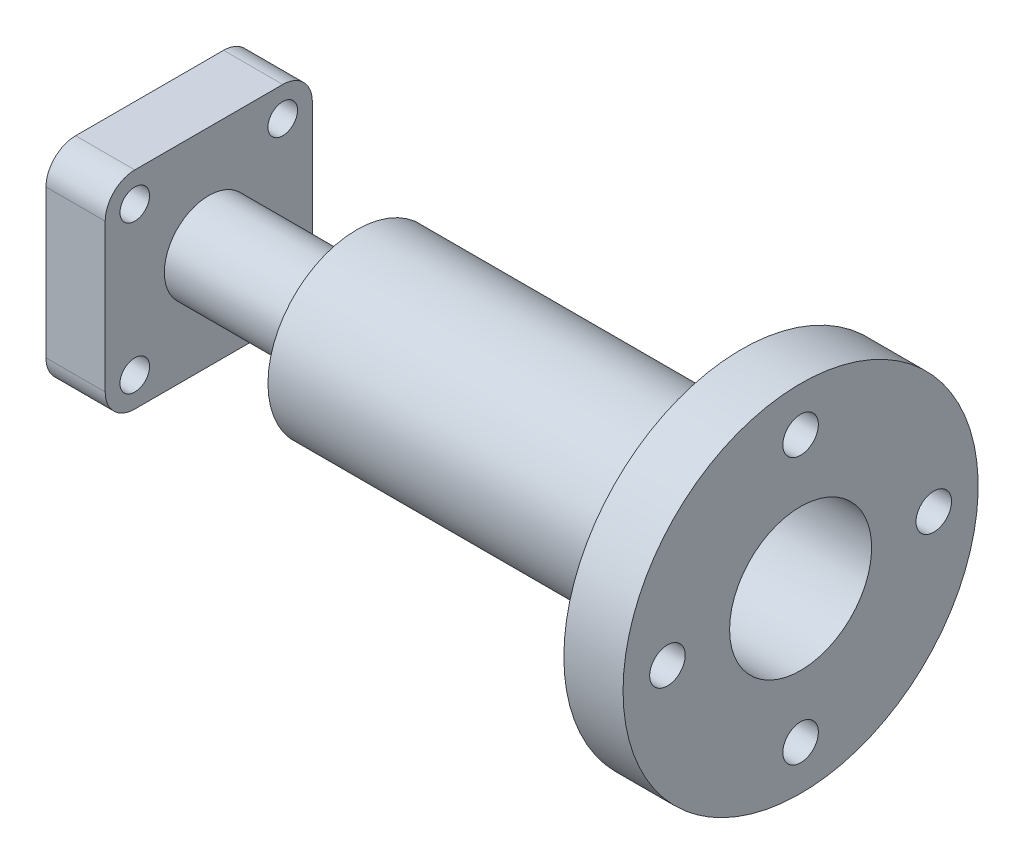
SolidWorks part; units mm, degrees
ref_plane "Front Plane" through (0, 0, 0) normal (0, 0, 1) x (1, 0, 0)
ref_plane "Top Plane" through (0, 0, 0) normal (0, 1, 0) x (1, 0, 0)
ref_plane "Right Plane" through (0, 0, 0) normal (1, 0, 0) x (0, 0, -1)
sketch "Sketch1" plane through (0, 0, 0) normal (0, 0, 1) x (1, 0, 0)
  line L0 (0, 0) -> (200, 0) construction
  line L1 (200, 24) -> (200, 60)
  line L2 (200, 60) -> (180, 60)
  line L3 (180, 60) -> (180, 30)
  line L4 (180, 30) -> (50, 30)
  line L5 (50, 30) -> (50, 15)
  line L6 (50, 15) -> (0, 15)
  line L7 (0, 15) -> (0, 9)
  line L9 (200, 24) -> (56, 24)
  line L10 (56, 24) -> (56, 9)
  line L11 (56, 9) -> (0, 9)
  point P3 (-6.0466, 15)
  point P14 (0, 0)
  dimension "D1" = 50
  dimension "D2" = 130
  dimension "D3" = 20
  dimension "D4" = 30
  dimension "D5" = 60
  dimension "D6" = 120
  dimension "D7" = 18
  dimension "D8" = 144
  dimension "D9" = 48
revolve "Revolve1" add sketch "Sketch1" angle 360 about L0
sketch "Sketch2" plane through (0, 0, 0) normal (-1, 0, 0) x (0, 0, 1)
  line L0 (0, 0) -> (35, 0) construction
  line L1 (-35, -35) -> (35, -35)
  line L2 (-35, -35) -> (-35, 35)
  line L3 (-35, 35) -> (35, 35)
  line L4 (35, -35) -> (35, 35)
  line L5 (-35, -35) -> (35, 35) construction
  line L6 (-35, 35) -> (35, -35) construction
  circle A0 centre (-25, 25) radius 5
  circle A1 centre (25, 25) radius 5
  circle A2 centre (25, -25) radius 5
  circle A3 centre (-25, -25) radius 5
  circle A4 centre (0, 0) radius 9 construction
  circle A5 centre (0, 0) radius 9
  point P0 (0, 0)
  dimension "D3" = 10
  dimension "D1" = 70
  dimension "D2" = 70
  dimension "D4" = 50
extrude "Boss-Extrude1" add sketch "Sketch2" along normal blind 20
fillet "Fillet1" radius 10 4 edges at (-10, -35, -35) (-10, -35, 35) (-10, 35, 35) (-10, 35, -35)
hole_wizard "Ø12.0mm Dowel Hole1" positions "Sketch6" profile "Sketch7" hole size "Ø12.0" standard "ANSI Metric"
sketch "Sketch6" plane through (200, 0, 0) normal (1, 0, 0) x (0, 0, -1)
  circle A0 centre (0, 0) radius 45 construction
  point P5 (0, 45)
  point P7 (-45, 0)
  point P9 (0, -45)
  point P11 (45, 0)
  dimension "D1" = 90
sketch "Sketch7" plane through (200, 0, -45) normal (0, 1, 0) x (0, 0, -1)
  line L0 (0, 0) -> (0, 23.6042)
  line L1 (0, 23.6042) -> (6, 19.999)
  line L2 (6, 19.999) -> (6, 0)
  line L5 (6, 0) -> (0, 0)
  line L10 (0, 23.6042) -> (-6, 19.999) construction
  line L11 (0, -6.35) -> (0, 107.95) construction
  dimension "Hole Dia." = 12
  dimension "Hole Depth" = 19.999
  dimension "Drill Angle" = 118
